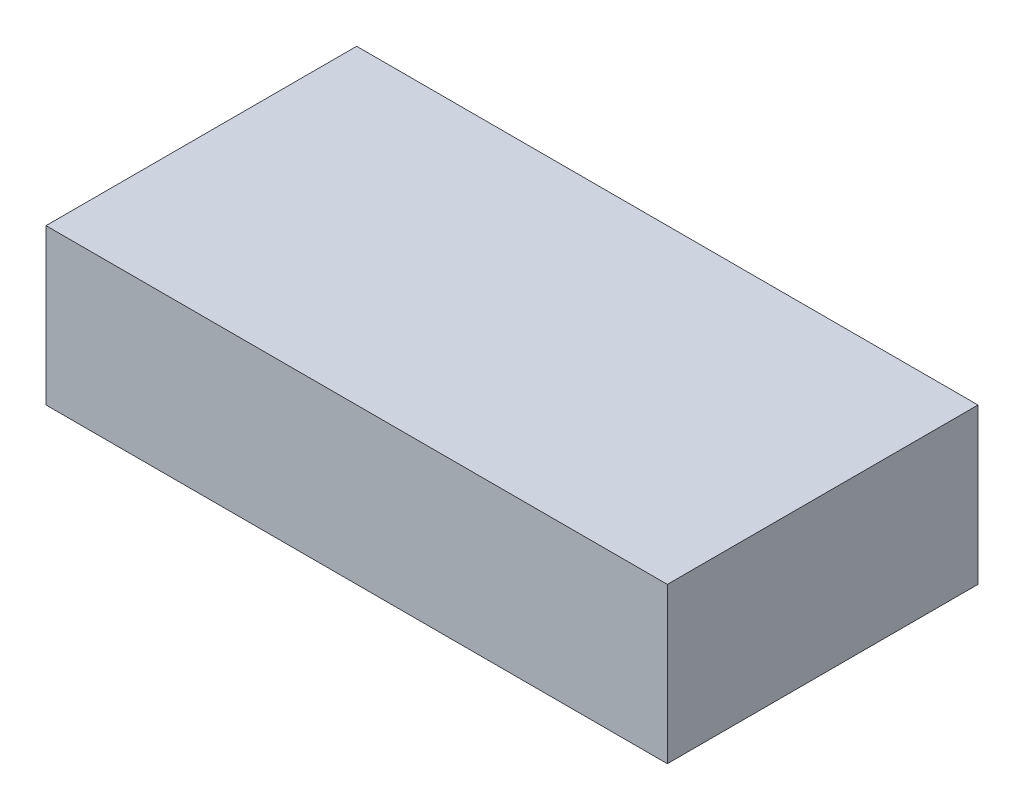
SolidWorks part; units mm, degrees
ref_plane "Front Plane" through (0, 0, 0) normal (0, 0, 1) x (1, 0, 0)
ref_plane "Top Plane" through (0, 0, 0) normal (0, 1, 0) x (1, 0, 0)
ref_plane "Right Plane" through (0, 0, 0) normal (1, 0, 0) x (0, 0, -1)
sketch "Sketch1" plane through (0, 0, 0) normal (0, 1, 0) x (1, 0, 0)
  line L1 (0, 0) -> (40, 0)
  line L2 (0, 0) -> (0, 20)
  line L3 (0, 20) -> (40, 20)
  line L4 (40, 0) -> (40, 20)
extrude "Boss-Extrude1" add sketch "Sketch1" along normal blind 10
